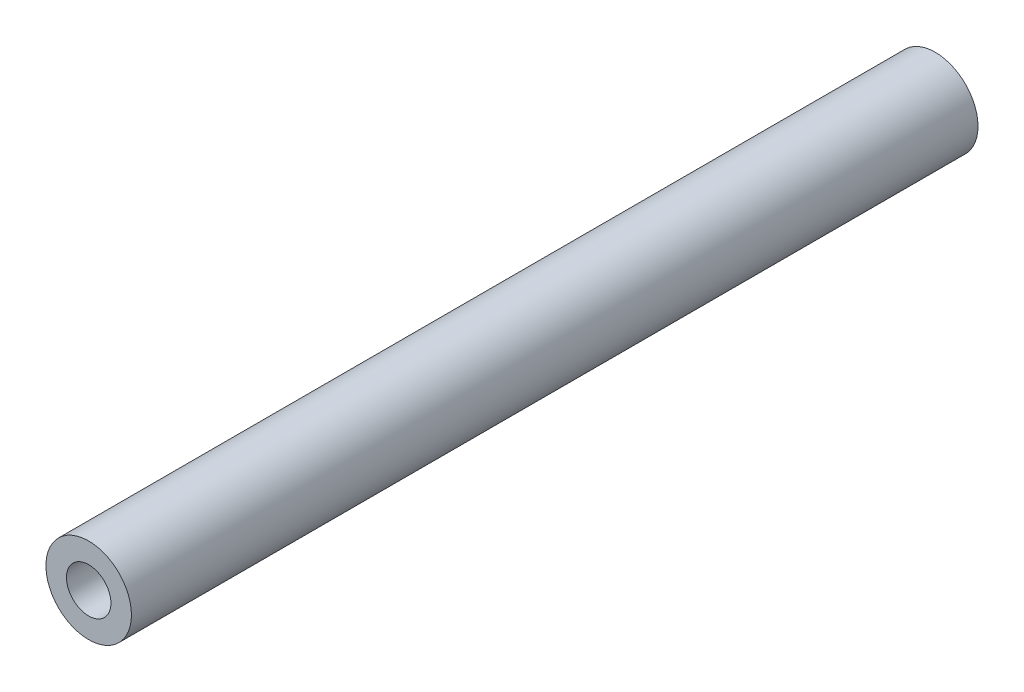
SolidWorks part; units mm, degrees
ref_plane "Front Plane" through (0, 0, 0) normal (0, 0, 1) x (1, 0, 0)
ref_plane "Top Plane" through (0, 0, 0) normal (0, 1, 0) x (1, 0, 0)
ref_plane "Right Plane" through (0, 0, 0) normal (1, 0, 0) x (0, 0, -1)
sketch "Sketch1" plane through (0, 0, 0) normal (0, 0, 1) x (1, 0, 0)
  circle A0 centre (0, 0) radius 2.5
extrude "Boss-Extrude1" add sketch "Sketch1" along normal blind 49.5
sketch "Sketch2" plane through (0, 0, 49.5) normal (0, 0, 1) x (1, 0, 0)
  point P0 (0, 0)
hole_wizard "M3x0.5 Tapped Hole1" positions "Sketch2" profile "Sketch3" tap size "M3x0.5" standard "JIS"
sketch "Sketch3" plane through (0, 0, 49.5) normal (1, 0, 0) x (0, -1, 0)
  line L0 (0, 0) -> (0, 8.7811)
  line L1 (0, 8.7811) -> (1.3, 8)
  line L2 (1.3, 8) -> (1.3, 0)
  line L5 (1.3, 0) -> (0, 0)
  line L10 (0, 8.7811) -> (-1.3, 8) construction
  line L11 (0, -6.35) -> (0, 107.95) construction
  dimension "Tap Drill Dia." = 2.6
  dimension "Tap Drill Depth" = 8
  dimension "Drill Angle" = 118
cosmetic thread "Hole Thread1" parameters "D1"=5, "D2"=3
sketch "Sketch4" plane through (0, 0, 0) normal (0, 0, -1) x (-1, 0, 0)
  point P0 (0, 0)
hole_wizard "M3x0.5 Tapped Hole2" positions "Sketch4" profile "Sketch5" tap size "M3x0.5" standard "JIS"
sketch "Sketch5" plane through (0, 0, 0) normal (1, 0, 0) x (0, 1, 0)
  line L0 (0, 0) -> (0, 8.7811)
  line L1 (0, 8.7811) -> (1.3, 8)
  line L2 (1.3, 8) -> (1.3, 0)
  line L5 (1.3, 0) -> (0, 0)
  line L10 (0, 8.7811) -> (-1.3, 8) construction
  line L11 (0, -6.35) -> (0, 107.95) construction
  dimension "Tap Drill Dia." = 2.6
  dimension "Tap Drill Depth" = 8
  dimension "Drill Angle" = 118
cosmetic thread "Hole Thread2" parameters "D1"=5, "D2"=3
